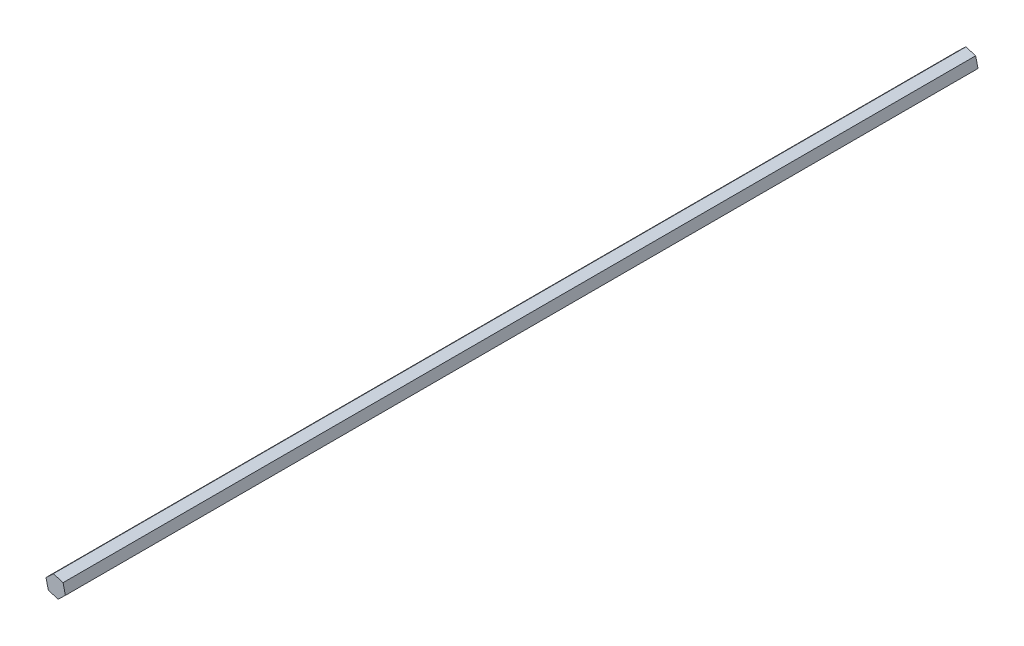
SolidWorks part; units mm, degrees
ref_plane "Front Plane" through (0, 0, 0) normal (0, 0, 1) x (1, 0, 0)
ref_plane "Top Plane" through (0, 0, 0) normal (0, 1, 0) x (1, 0, 0)
ref_plane "Right Plane" through (0, 0, 0) normal (1, 0, 0) x (0, 0, -1)
sketch "Sketch1" plane through (0, 0, 0) normal (0, 0, 1) x (1, 0, 0)
  line L1 (7.0265, -2.0956) -> (5.3281, 5.0373)
  line L2 (5.3281, 5.0373) -> (-1.6984, 7.1329)
  line L3 (-1.6984, 7.1329) -> (-7.0265, 2.0956)
  line L4 (-7.0265, 2.0956) -> (-5.3281, -5.0373)
  line L5 (-5.3281, -5.0373) -> (1.6984, -7.1329)
  line L6 (1.6984, -7.1329) -> (7.0265, -2.0956)
  circle A0 centre (0, 0) radius 6.35 construction
extrude "Boss-Extrude1" add sketch "Sketch1" along normal blind 660.4
